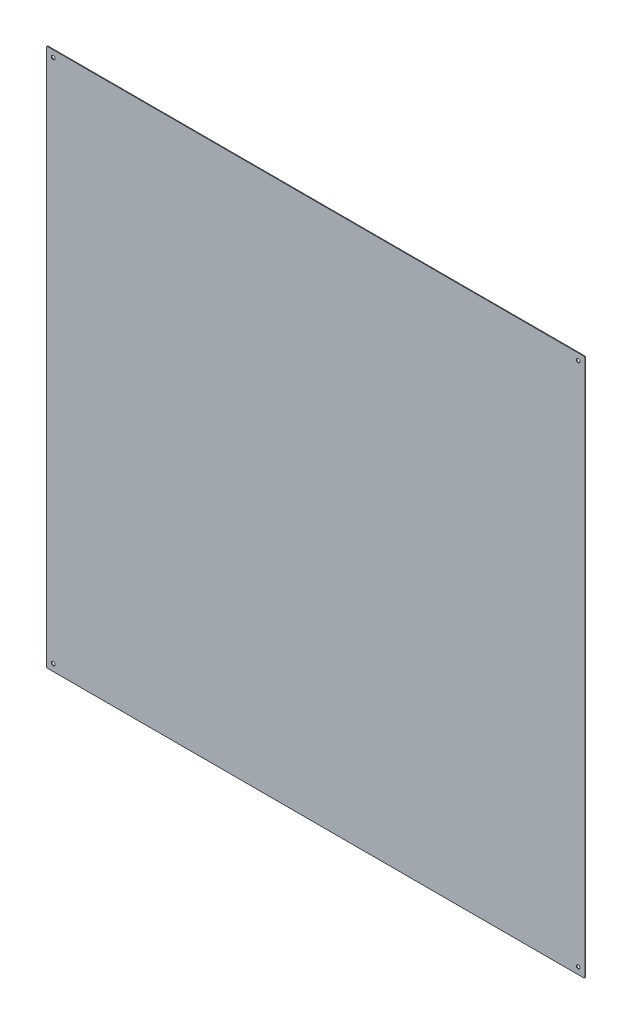
SolidWorks part; units mm, degrees
material "Plain Carbon Steel"
ref_plane "Front Plane" through (0, 0, 0) normal (0, 0, 1) x (1, 0, 0)
ref_plane "Top Plane" through (0, 0, 0) normal (0, 1, 0) x (1, 0, 0)
ref_plane "Right Plane" through (0, 0, 0) normal (1, 0, 0) x (0, 0, -1)
sketch "Sketch1" plane through (0, 0, 6) normal (0, 0, 1) x (1, 0, 0)
  line L1 (-602.5, 602.5) -> (602.5, 602.5)
  line L2 (-602.5, 602.5) -> (-602.5, -602.5)
  line L3 (-602.5, -602.5) -> (602.5, -602.5)
  line L4 (602.5, 602.5) -> (602.5, -602.5)
  line L5 (-602.5, 602.5) -> (602.5, -602.5) construction
  line L6 (-602.5, -602.5) -> (602.5, 602.5) construction
  point P0 (0, 0)
  dimension "D1" = 1205
extrude "Boss-Extrude1" add sketch "Sketch1" along normal blind 1.5
fillet "Fillet1" radius 3 4 edges at (-602.5, 602.5, 6.75) (602.5, 602.5, 6.75) (602.5, -602.5, 6.75) (-602.5, -602.5, 6.75)
sketch "Sketch2" plane through (0, 0, 6) normal (0, 0, -1) x (-1, 0, 0)
  circle A0 centre (587.3223, -587.3223) radius 4
  circle A1 centre (-587.3223, -587.3223) radius 4
  circle A2 centre (-587.3223, 587.3223) radius 4
  circle A3 centre (587.3223, 587.3223) radius 4
  circle A4 centre (-587.3223, 587.3223) radius 2.4 construction
  circle A5 centre (-587.3223, -587.3223) radius 2.4 construction
  circle A6 centre (587.3223, -587.3223) radius 2.4 construction
  dimension "D1" = 8
extrude "Cut-Extrude1" cut sketch "Sketch2" against normal through all
